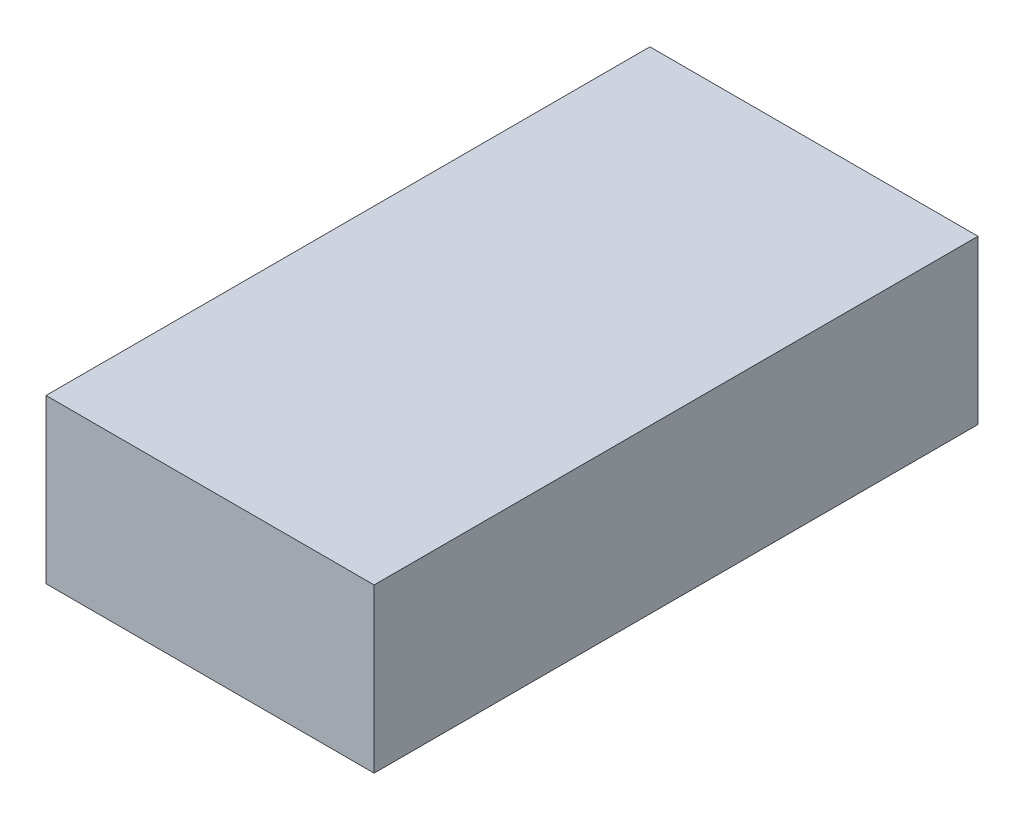
SolidWorks part; units mm, degrees
ref_plane "前视基准面" through (0, 0, 0) normal (0, 0, 1) x (1, 0, 0)
ref_plane "上视基准面" through (0, 0, 0) normal (0, 1, 0) x (1, 0, 0)
ref_plane "右视基准面" through (0, 0, 0) normal (1, 0, 0) x (0, 0, -1)
sketch "草图1" plane through (0, 0, 0) normal (0, 0, 1) x (1, 0, 0)
  line L1 (0, 0) -> (81.5, 0)
  line L2 (0, 0) -> (0, 40.5)
  line L3 (0, 40.5) -> (81.5, 40.5)
  line L4 (81.5, 0) -> (81.5, 40.5)
  dimension "D1" = 81.5
  dimension "D2" = 40.5
extrude "凸台-拉伸1" add sketch "草图1" along normal blind 150
